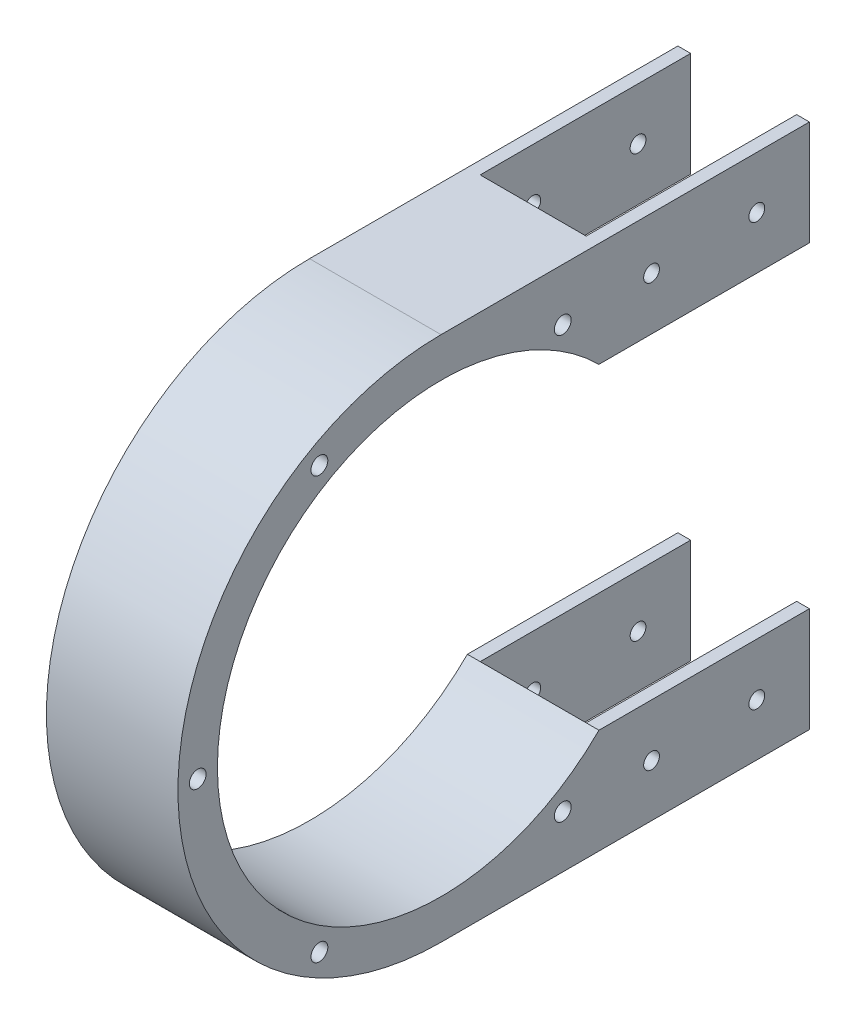
SolidWorks part; units mm, degrees
ref_plane "Front Plane" through (0, 0, 0) normal (0, 0, 1) x (1, 0, 0)
ref_plane "Top Plane" through (0, 0, 0) normal (0, 1, 0) x (1, 0, 0)
ref_plane "Right Plane" through (0, 0, 0) normal (1, 0, 0) x (0, 0, -1)
sketch "草图1" plane through (0, 0, 0) normal (1, 0, 0) x (0, 0, -1)
  line L0 (-50, 0) -> (-42.5, 0)
  line L1 (30, 30.104) -> (30, 50)
  line L2 (30, 50) -> (0, 50)
  line L3 (0, 50) -> (30, 50)
  line L4 (30, -30.104) -> (30, -50)
  line L5 (30, -50) -> (0, -50)
  arc A0 (0, 50) -> (0, -50) centre (0, 0) ccw
  arc A1 (30, 30.104) -> (30, -30.104) centre (0, 0) ccw
  circle A2 centre (-46.25, 0) radius 1.6
  circle A3 centre (-23.125, 40.0537) radius 1.6
  circle A4 centre (23.125, 40.0537) radius 1.6
  circle A6 centre (23.125, -40.0537) radius 1.6
  circle A7 centre (-23.125, -40.0537) radius 1.6
  circle A8 centre (46.25, 0) radius 1.6 [skipped]
  point P25 (0, 0)
  dimension "D1" = 100
  dimension "D2" = 85
  dimension "D3" = 3.2
  dimension "D4" = 6
extrude "凸台-拉伸1" add sketch "草图1" along normal blind 25 contours A2 L0 A1 L1 L2 A0 A4 A3 | A2 L0 A0 L5 L4 A1 A7 A6
sketch "草图2" plane through (0, 0, -30) normal (0, 0, -1) x (-1, 0, 0)
  line L1 (-25, 50) -> (-22.57, 50)
  line L2 (-25, 50) -> (-25, 30.104)
  line L3 (-25, 30.104) -> (-22.57, 30.104)
  line L4 (-22.57, 50) -> (-22.57, 30.104)
  line L5 (-25, 30.104) -> (0, 30.104) construction
  line L6 (0, 0) -> (-70.7097, 0) construction
  line L7 (0, 50) -> (-2.43, 50)
  line L8 (0, 50) -> (0, 30.104)
  line L9 (0, 30.104) -> (-2.43, 30.104)
  line L10 (-2.43, 50) -> (-2.43, 30.104)
  line L11 (-2.43, -50) -> (-2.43, -30.104)
  line L12 (0, -30.104) -> (-2.43, -30.104)
  line L13 (0, -50) -> (0, -30.104)
  line L14 (0, -50) -> (-2.43, -50)
  line L15 (-22.57, -50) -> (-22.57, -30.104)
  line L16 (-25, -30.104) -> (-22.57, -30.104)
  line L17 (-25, -50) -> (-25, -30.104)
  line L18 (-25, -50) -> (-22.57, -50)
  point P6 (-22.57, 40.052)
  point P14 (-2.43, 40.052)
  dimension "D1" = 19.896
  dimension "D2" = 2.43
  dimension "D3" = 19.896
  dimension "D4" = 2.43
  dimension "D5" = 2.43
  dimension "D6" = 20.14
extrude "凸台-拉伸2" add sketch "草图2" along normal blind 40
sketch "草图4" plane through (25, 0, 0) normal (1, 0, 0) x (0, 0, -1)
  line L0 (70, -30.104) -> (70, -50) construction
  line L1 (70, -30.104) -> (30, -30.104) construction
  line L2 (0, 0) -> (27.5548, 0) construction
  circle A0 centre (60, -40.104) radius 1.5
  circle A1 centre (40, -40.104) radius 1.5
  circle A2 centre (40, 40.104) radius 1.5
  circle A3 centre (60, 40.104) radius 1.5
  dimension "D1" = 3
  dimension "D2" = 3
  dimension "D3" = 10
  dimension "D4" = 10
  dimension "D5" = 10
  dimension "D6" = 20
extrude "切除-拉伸4" cut sketch "草图4" against normal through all
